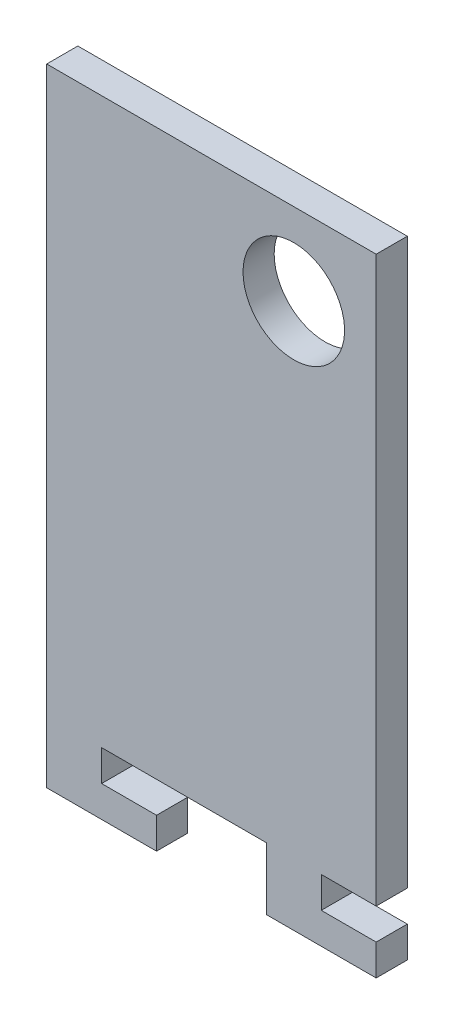
SolidWorks part; units mm, degrees
ref_plane "Front Plane" through (0, 0, 0) normal (0, 0, 1) x (1, 0, 0)
ref_plane "Top Plane" through (0, 0, 0) normal (0, 1, 0) x (1, 0, 0)
ref_plane "Right Plane" through (0, 0, 0) normal (1, 0, 0) x (0, 0, -1)
sketch "Sketch1" plane through (0, 0, 0) normal (0, 0, 1) x (1, 0, 0)
  line L1 (0, 0) -> (50.8, 0)
  line L2 (0, 0) -> (0, 96.6555)
  line L3 (0, 96.6555) -> (50.8, 96.6555)
  line L4 (50.8, 0) -> (50.8, 96.6555)
  line L5 (0, 0) -> (50.8, 96.6555) construction
  line L6 (0, 96.6555) -> (50.8, 0) construction
  point P4 (25.4, 48.3277)
  dimension "D2" = 50.8
  dimension "D1" = 96.6555
extrude "Boss-Extrude1" add sketch "Sketch1" along normal blind 4.8
sketch "Sketch3" plane through (0, 0, 0) normal (0, 0, -1) x (-1, 0, 0)
  line L0 (0, 96.6555) -> (0, 0) construction
  line L1 (0, 0) -> (-50.8, 0) construction
  circle A0 centre (-38.1, 84.0277) radius 7.8277
  dimension "D1" = 15.6555
  dimension "D2" = 38.1
  dimension "D3" = 84.0277
extrude "Cut-Extrude2" cut sketch "Sketch3" against normal through all contours A0
sketch "Sketch4" plane through (0, 0, 0) normal (0, 0, -1) x (-1, 0, 0)
  line L0 (-50.8, 0) -> (-50.8, 96.6555) construction
  line L1 (-50.8, 4.8) -> (-42.3333, 4.8)
  line L2 (-50.8, 4.8) -> (-50.8, 9.6)
  line L3 (-50.8, 9.6) -> (-42.3333, 9.6)
  line L4 (-42.3333, 4.8) -> (-42.3333, 9.6)
  line L5 (-50.8, 4.8) -> (-42.3333, 9.6) construction
  line L6 (-50.8, 9.6) -> (-42.3333, 4.8) construction
  line L7 (-42.3333, 4.8) -> (-42.3333, 0) construction
  line L8 (-16.9333, 4.8) -> (-8.4667, 4.8)
  line L9 (-16.9333, 4.8) -> (-16.9333, 9.6)
  line L10 (-16.9333, 9.6) -> (-8.4667, 9.6)
  line L11 (-8.4667, 4.8) -> (-8.4667, 9.6)
  line L12 (-16.9333, 4.8) -> (-8.4667, 9.6) construction
  line L13 (-16.9333, 9.6) -> (-8.4667, 4.8) construction
  line L14 (0, 0) -> (-50.8, 0) construction
  line L15 (-8.4667, 4.8) -> (-8.4667, 0) construction
  line L16 (-8.4667, 4.8) -> (0, 4.8) construction
  line L18 (0, 96.6555) -> (0, 0) construction
  line L19 (-16.9333, 4.8) -> (-42.3333, 4.8) construction
  point P4 (-46.5667, 7.2)
  point P11 (-12.7, 7.2)
  line M16 (-50.8, 96.6555) -> (-50.8, 0)
  dimension "D1" = 4.8
  dimension "D2" = 4.8
  dimension "D3" = 8.4667
  dimension "D4" = 8.4667
extrude "Cut-Extrude4" cut sketch "Sketch4" against normal through all contours L1 L4 L3 M16 | L9 L8 L11 L10
sketch "Sketch5" plane through (0, 0, 0) normal (0, 0, -1) x (-1, 0, 0)
  line L0 (0, 0) -> (-50.8, 0) construction
  line L1 (-16.9333, 0) -> (-33.8667, 0)
  line L2 (-16.9333, 0) -> (-16.9333, 9.6)
  line L3 (-16.9333, 9.6) -> (-33.8667, 9.6)
  line L4 (-33.8667, 0) -> (-33.8667, 9.6)
  line L5 (-16.9333, 0) -> (-33.8667, 9.6) construction
  line L6 (-16.9333, 9.6) -> (-33.8667, 0) construction
  line L7 (0, 96.6555) -> (0, 0) construction
  point P4 (-25.4, 4.8)
  dimension "D1" = 9.6
  dimension "D2" = 16.9333
  dimension "D3" = 16.9333
extrude "Cut-Extrude5" cut sketch "Sketch5" against normal through all
equation "\"MDF\"= 4.8mm"
equation "\"Foamcore\"= 4.6mm"
equation "\"PCB\" = 1.6mm"
equation "\"GMaterial\"= \"MDF\""
equation "\"BaseWidth\" = 10in"
equation "\"SkidLength\" = 1in"
equation "\"SkidClearance\" = 0.4in"
equation "\"MotorMountLength\" = 2in"
equation "\"MotorMountWidth\" = \"GMaterial\""
equation "\"MotorMountHeight\" = 2in"
equation "\"UnoStackWidth\" = 77.4mm"
equation "\"UnoStackLength\" = 79.8mm"
equation "\"UnoStackHeight\" = 34.2mm"
equation "\"TallHexRiserHeight\" = 22.2mm"
equation "\"PingPongBallSize\" = 40mm"
equation "\"BarrelLength\" = 9in"
equation "\"BarrelSize\" = \"PingPongBallSize\""
equation "\"PlatformLength\" = 4in"
equation "\"PlatformWidth\" = 5in"
equation "\"WheelWidth\" = 26mm"
equation "\"WheelDiameter\" = 63mm"
equation "\"ServoMountLength\"=1.53774"
equation "\"ServoGearHeight\" = 0.95907867in"
equation "\"PlatformMountHeight\"=3.19"
equation "\"PivotHoleRadius\"= 0.616358"
equation "\"D1@Sketch1\"=\"MDF\"+\"PivotHoleRadius\"+3"
equation "\"D1@Sketch3\"= \"PivotHoleRadius\""
equation "\"D2@Sketch3\"=3/2"
equation "\"D3@Sketch3\"=\"PivotHoleRadius\"/2 +3"
equation "\"D1@Sketch4\"=\"GMaterial\""
equation "\"D2@Sketch4\"=\"GMaterial\""
equation "\"D4@Sketch4\"=1/3"
equation "\"D1@Sketch5\"=\"GMaterial\"*2"
